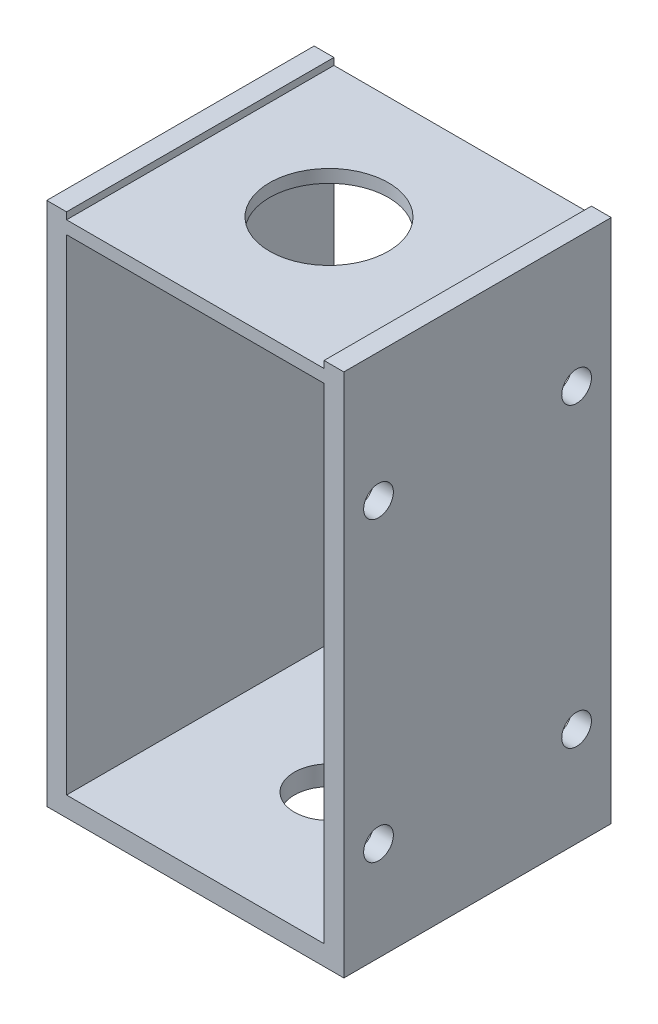
SolidWorks part; units mm, degrees
ref_plane "前视基准面" through (0, 0, 0) normal (0, 0, 1) x (1, 0, 0)
ref_plane "上视基准面" through (0, 0, 0) normal (0, 1, 0) x (1, 0, 0)
ref_plane "右视基准面" through (0, 0, 0) normal (1, 0, 0) x (0, 0, -1)
sketch "草图2" plane through (0, 0, 0) normal (0, 0, 1) x (1, 0, 0)
  line L1 (-15, 26.5) -> (15, 26.5)
  line L2 (-15, 26.5) -> (-15, -26.5)
  line L3 (-15, -26.5) -> (15, -26.5)
  line L4 (15, 26.5) -> (15, -26.5)
  line L5 (-15, 26.5) -> (15, -26.5) construction
  line L6 (-15, -26.5) -> (15, 26.5) construction
  point P0 (0, 0)
  dimension "D1" = 53
  dimension "D2" = 30
extrude "拉伸-薄壁1" add sketch "草图2" along normal blind 27 thin
sketch "草图3" plane through (0, 26.5, 0) normal (0, 1, 0) x (1, 0, 0)
  line L0 (15, 0) -> (-15, 0) construction
  line L1 (-13, 0) -> (13, 0)
  line L2 (-13, 0) -> (-13, -27)
  line L3 (-13, -27) -> (13, -27)
  line L4 (13, 0) -> (13, -27)
  line L5 (15, -27) -> (-15, -27) construction
  line L6 (-15, -27) -> (-15, 0) construction
  line L7 (15, -27) -> (15, 0) construction
  dimension "D1" = 2
  dimension "D2" = 2
extrude "切除-拉伸1" cut sketch "草图3" against normal blind 0.7
sketch "草图4" plane through (0, -26.5, 0) normal (0, -1, 0) x (1, 0, 0)
  line L0 (-15, 27) -> (15, 0) construction
  circle A0 centre (0, 13.5) radius 3.5
  dimension "D1" = 7
extrude "切除-拉伸2" cut sketch "草图4" against normal blind 38
sketch "草图5" plane through (15, 0, 0) normal (1, 0, 0) x (0, 0, -1)
  line L0 (-13.5, 26.5) -> (-13.5, -41.3146) construction
  line L1 (-27, 26.5) -> (0, 26.5) construction
  line L2 (-27, -26.5) -> (0, -26.5) construction
  circle A0 centre (-3.5, -16.5) radius 1.5
  circle A1 centre (-3.5, 13.5) radius 1.5
  circle A2 centre (-23.5, -16.5) radius 1.5
  circle A3 centre (-23.5, 13.5) radius 1.5
  dimension "D1" = 10
  dimension "D2" = 30
  dimension "D3" = 20
  dimension "D4" = 20
extrude "切除-拉伸3" cut sketch "草图5" against normal blind 3
sketch "草图6" plane through (0, 25.8, 0) normal (0, 1, 0) x (1, 0, 0)
  line L0 (-13, 0) -> (13, -27) construction
  circle A0 centre (0, -13.5) radius 6
  dimension "D1" = 12
extrude "切除-拉伸4" cut sketch "草图6" against normal blind 3
